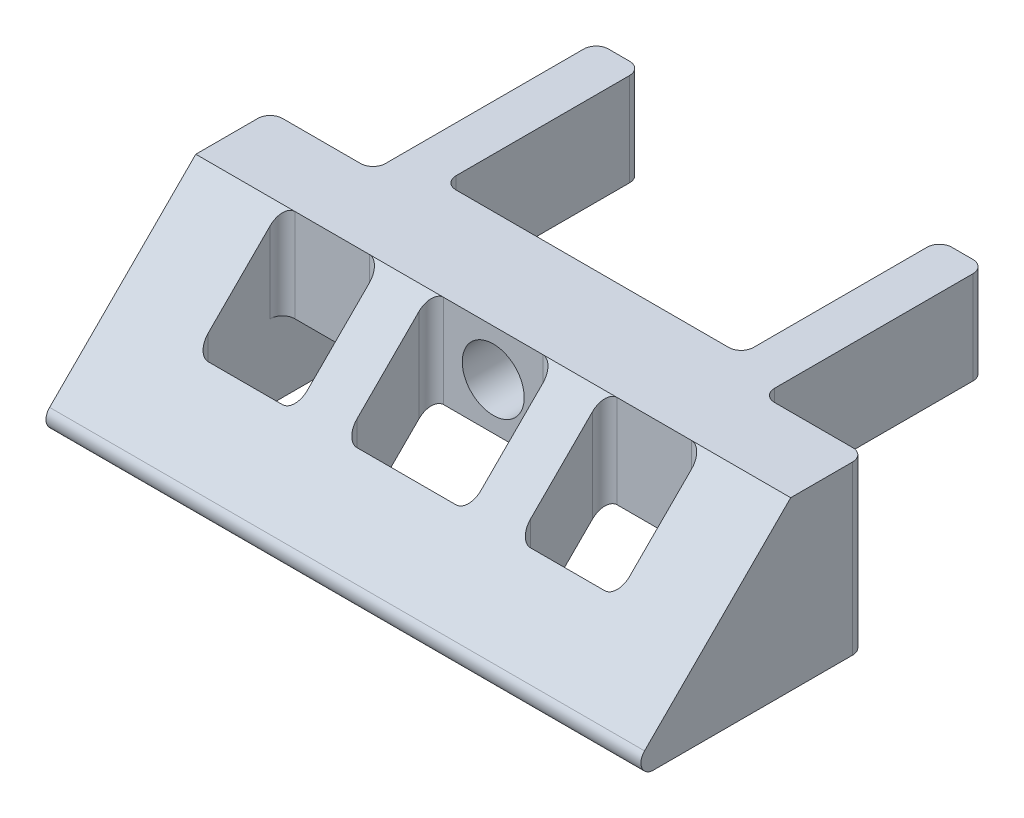
SolidWorks part; units mm, degrees
ref_plane "Front Plane" through (0, 0, 0) normal (0, 0, 1) x (1, 0, 0)
ref_plane "Top Plane" through (0, 0, 0) normal (0, 1, 0) x (1, 0, 0)
ref_plane "Right Plane" through (0, 0, 0) normal (1, 0, 0) x (0, 0, -1)
sketch "Sketch1" plane through (0, 0, 0) normal (0, 1, 0) x (1, 0, 0)
  line L0 (0, 24) -> (8.3, 24)
  line L1 (0, 0) -> (48, 0)
  line L2 (0, 0) -> (0, 24)
  line L3 (0, 24) -> (48, 24)
  line L4 (48, 0) -> (48, 24)
  line L5 (0, 24) -> (0, 6)
  line L6 (0, 6) -> (8.3, 6)
  line L7 (8.3, 24) -> (8.3, 6)
  line L8 (48, 24) -> (39.7, 24)
  line L9 (48, 24) -> (48, 6)
  line L10 (48, 6) -> (39.7, 6)
  line L11 (39.7, 24) -> (39.7, 6)
  line L12 (12, 24) -> (36, 24)
  line L13 (12, 24) -> (12, 8)
  line L14 (12, 8) -> (36, 8)
  line L15 (36, 24) -> (36, 8)
  point P17 (0, 0)
  point P18 (39.7, 4.2512)
  point P19 (0, 0)
  dimension "D1" = 48
  dimension "D2" = 24
  dimension "D3" = 18
  dimension "D4" = 18
  dimension "D5" = 24
  dimension "D6" = 3.7
  dimension "D7" = 3.7
  dimension "D8" = 8.3
  dimension "D9" = 8
extrude "Boss-Extrude2" add sketch "Sketch1" along normal blind 7.5 contours L3 L15 L14 L13 L7 L6 L2 L1 L4 L10 L11
sketch "Sketch3" plane through (48, 0, 0) normal (1, 0, 0) x (0, 0, -1)
  line L0 (0, 0) -> (-6, -6)
  line L1 (-6, -6) -> (-13.5, -6)
  line L2 (-13.5, -6) -> (0, 7.5)
  line L3 (0, 7.5) -> (0, 0) construction
  line L4 (0, 0) -> (0, 7.5)
  point P3 (-12.3007, -5.5846)
  point P8 (0, 7.5)
  point P9 (0, 5.7288)
  point P10 (0, 0)
  point P11 (0, 6.0655)
  dimension "D1" = 7.5
  dimension "D2" = 6
  dimension "D3" = 6
  dimension "D4" = 7.5
extrude "Boss-Extrude3" add sketch "Sketch3" against normal up to surface (48 mm away) up to face at (0, 3.75, -3)
sketch "Sketch16" plane through (48, 0, 0) normal (1, 0, 0) x (0, 0, -1)
  line L0 (-6, -6) -> (6, -6)
  line L1 (6, -6) -> (6, 0)
  line L2 (6, 7.5) -> (6, 0) construction
  line L3 (6, 7.5) -> (6, 0) construction
  line L4 (6, 0) -> (0, 0)
  line L5 (0, 0) -> (-6, -6)
  point P10 (0, 0)
  point P11 (6.6899, -6)
extrude "Boss-Extrude4" add sketch "Sketch16" against normal blind 7
sketch "Sketch4" plane through (0, -6, 0) normal (0, -1, 0) x (1, 0, 0)
  line L0 (24, 13.5) -> (24, -8) construction
  line L1 (0, 13.5) -> (48, 13.5) construction
  line L2 (12, -8) -> (36, -8) construction
  line L4 (7, 7) -> (15, 7)
  line L5 (7, 7) -> (7, 0)
  line L6 (7, 0) -> (15, 0)
  line L7 (15, 7) -> (15, 0)
  line L8 (0, 0) -> (41, 0) construction
  line L9 (41, 0) -> (33, 0)
  line L10 (0, 6) -> (0, 0) construction
  line L11 (33, 7) -> (33, 0)
  line L12 (41, 7) -> (33, 7)
  line L13 (41, 7) -> (41, 0)
  line L15 (19, 7) -> (29, 7)
  line L16 (19, 7) -> (19, 0)
  line L17 (19, 0) -> (29, 0)
  line L18 (29, 7) -> (29, 0)
  dimension "D1" = 8
  dimension "D2" = 7
  dimension "D3" = 4
  dimension "D4" = 4
  dimension "D5" = 7
extrude "Cut-Extrude2" cut sketch "Sketch4" against normal up to surface (13.5 mm away)
hole_wizard "M6x1.0 Tapped Hole4" positions "Sketch14" profile "Sketch15" tap size "M6x1.0" standard "ANSI Metric" end condition through all
sketch "Sketch14" plane through (0, 0, -8) normal (0, 0, -1) x (-1, 0, 0)
  line L0 (-12, 7.5) -> (-36, 7.5) construction
  line L1 (-36, 7.5) -> (-36, 0) construction
  point P0 (-24, 3.75)
  dimension "D1" = 3.75
  dimension "D2" = 12
sketch "Sketch15" plane through (24, 3.75, -8) normal (1, 0, 0) x (0, 1, 0)
  line L0 (0, 0) -> (0, 21.5)
  line L1 (0, 21.5) -> (2.5, 21.5)
  line L2 (2.5, 21.5) -> (2.5, 0)
  line L5 (2.5, 0) -> (0, 0)
  line L11 (0, -6.35) -> (0, 107.95) construction
  dimension "Thru Tap Drill Dia." = 5
  dimension "Thru Tap Drill Depth" = 21.5
cosmetic thread "Hole Thread4" parameters "D2"=6
ref_plane "Plane2" through (24, 0, 0) normal (-1, 0, 0) x (0, 0, 1)
mirror "Mirror1" about plane through (24, 0, 0) normal (-1, 0, 0) of "Boss-Extrude4"
fillet "Fillet1" radius 1 29 edges at (19, -6, 6.5) (29, 3.75, 0) (29, -2.75, 7) (19, -2.75, 7) (19, 3.75, 0) (7, -3, -6) (39.7, 3.75, -24) (39.7, 3.75, -6) (48, 0.75, -6) (0, 0.75, -6) (8.3, 3.75, -6) (8.3, 3.75, -24) (12, 3.75, -24) (12, 3.75, -8) (36, 3.75, -8) (36, 3.75, -24) (24, -6, 13.5) (41, -3, -6) (29, -6, 6.5) (15, -6, 6.5) (15, 3.75, 0) (15, -2.75, 7) (7, -2.75, 7) (7, 3.75, 0) (33, -6, 6.5) (33, -2.75, 7) (33, 3.75, 0) (41, 3.75, 0) (41, -2.75, 7)
